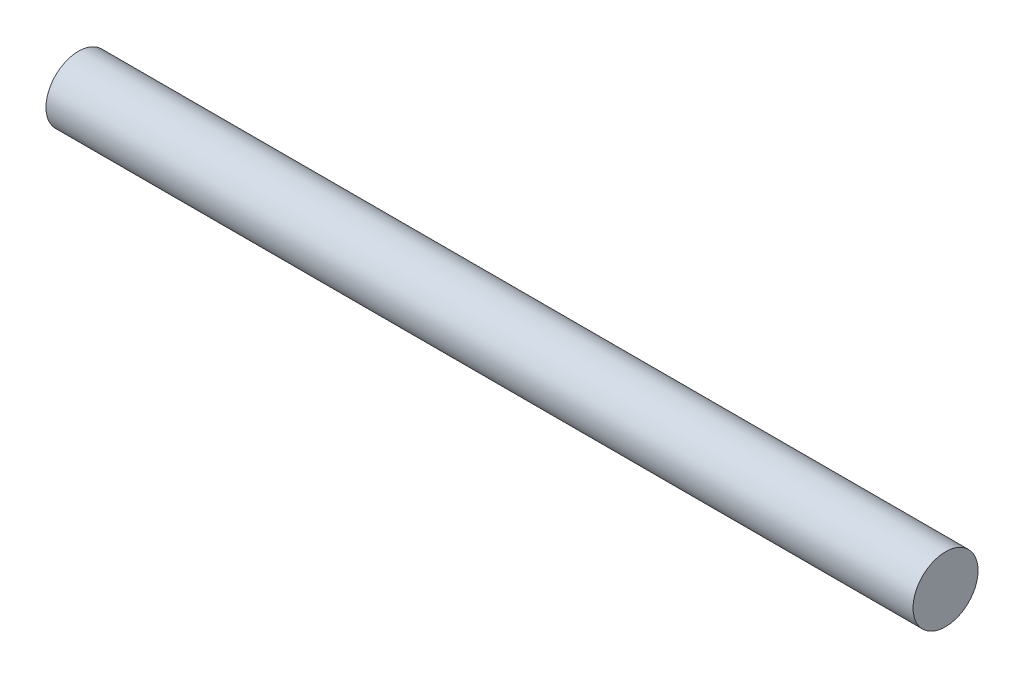
SolidWorks part; units mm, degrees
material "1.0503 (C45)"
ref_plane "Plan de face" through (0, 0, 0) normal (0, 0, 1) x (1, 0, 0)
ref_plane "Plan de dessus" through (0, 0, 0) normal (0, 1, 0) x (1, 0, 0)
ref_plane "Plan de droite" through (0, 0, 0) normal (1, 0, 0) x (0, 0, -1)
sketch "Esquisse1" plane through (0, 0, 0) normal (0, 1, 0) x (1, 0, 0)
  line L0 (-80, 0) -> (80, 0) construction
  line L2 (-80, 0) -> (80, 0)
  line L3 (-80, 0) -> (-80, 6)
  line L4 (-80, 6) -> (80, 6)
  line L5 (80, 0) -> (80, 6)
  dimension "D1" = 12
  dimension "D2" = 160
revolve "Révolution1" add sketch "Esquisse1" angle 360 about L0
